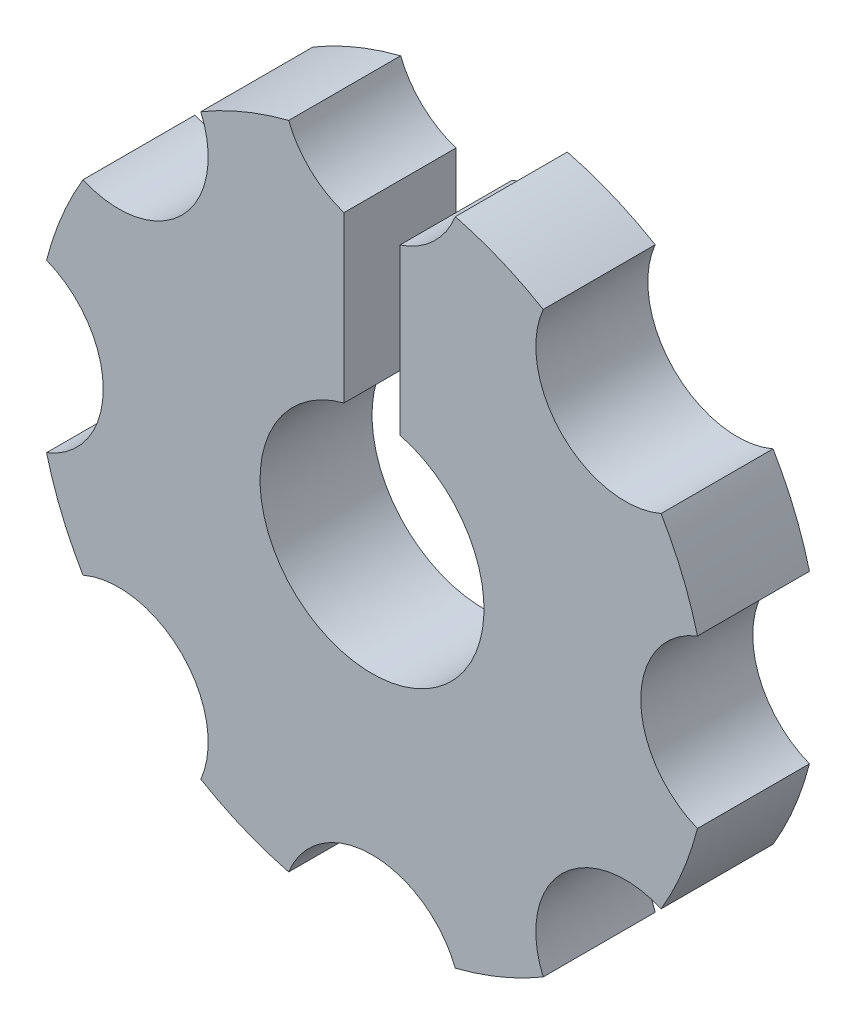
SolidWorks part; units mm, degrees
material "Aleación 1060"
ref_plane "Alzado" through (0, 0, 0) normal (0, 0, 1) x (1, 0, 0)
ref_plane "Planta" through (0, 0, 0) normal (0, 1, 0) x (1, 0, 0)
ref_plane "Vista lateral" through (0, 0, 0) normal (1, 0, 0) x (0, 0, -1)
sketch "Croquis1" plane through (0, 0, 0) normal (0, 0, 1) x (1, 0, 0)
  circle A0 centre (0, 0) radius 3.175
  circle A1 centre (0, 0) radius 9.525
  dimension "D1" = 6.35
  dimension "D2" = 19.05
extrude "Saliente-Extruir1" add sketch "Croquis1" along normal blind 3.175
sketch "Croquis2" plane through (0, 0, 3.175) normal (0, 0, 1) x (1, 0, 0)
  line L0 (0, 0) -> (-10.16, 0) construction
  circle A0 centre (-10.16, 0) radius 2.54
  circle A1 centre (-7.1842, 7.1842) radius 2.54
  circle A2 centre (0, 10.16) radius 2.54
  circle A3 centre (7.1842, 7.1842) radius 2.54
  circle A4 centre (10.16, 0) radius 2.54
  circle A5 centre (7.1842, -7.1842) radius 2.54
  circle A6 centre (0, -10.16) radius 2.54
  circle A7 centre (-7.1842, -7.1842) radius 2.54
  point P21 (0, 0)
  dimension "D2" = 5.08
  dimension "D1" = 10.16
  dimension "D3" = 8
extrude "Cortar-Extruir1" cut sketch "Croquis2" against normal blind 3.175
sketch "Croquis3" plane through (0, 0, 0) normal (0, 1, 0) x (1, 0, 0)
  line L0 (0, 0) -> (0, -3.175) construction
  line L1 (-2.3626, -3.175) -> (2.3626, -3.175) construction
  line L2 (0.7937, 0) -> (-0.7937, 0)
  line L3 (2.3626, 0) -> (-2.3626, 0) construction
  line L4 (-0.7937, 0) -> (-0.7937, -3.175)
  line L5 (-0.7937, -3.175) -> (0.7938, -3.175)
  line L6 (0.7937, 0) -> (0.7938, -3.175)
  dimension "D1" = 0.7937
extrude "Cortar-Extruir2" cut sketch "Croquis3" along normal through all
